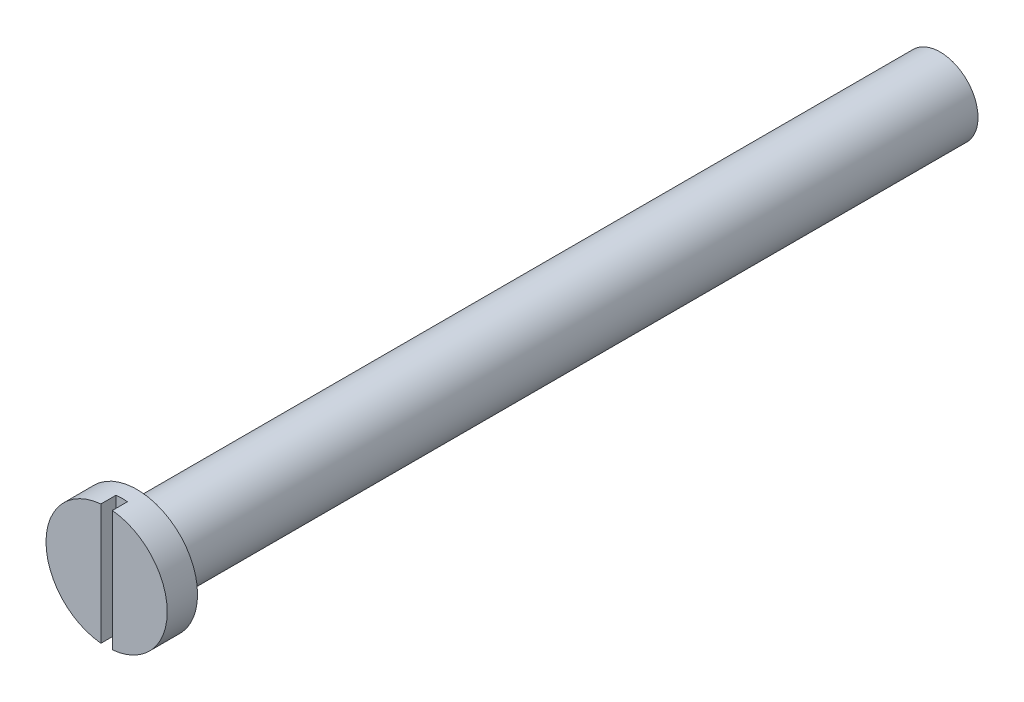
SolidWorks part; units mm, degrees
ref_plane "前视基准面" through (0, 0, 0) normal (0, 0, 1) x (1, 0, 0)
ref_plane "上视基准面" through (0, 0, 0) normal (0, 1, 0) x (1, 0, 0)
ref_plane "右视基准面" through (0, 0, 0) normal (1, 0, 0) x (0, 0, -1)
sketch "草图1" plane through (0, 0, 0) normal (0, 0, 1) x (1, 0, 0)
  circle A0 centre (0, 0) radius 5
  dimension "D1" = 10
extrude "凸台-拉伸1" add sketch "草图1" along normal blind 106
cosmetic thread "装饰螺纹线2" parameters "D1"=10, "D2"=4.134
sketch "草图2" plane through (0, 0, 106) normal (0, 0, 1) x (1, 0, 0)
  circle A0 centre (0, 0) radius 8
  dimension "D1" = 16
extrude "凸台-拉伸2" add sketch "草图2" along normal blind 4
sketch "草图4" plane through (0, 0, 110) normal (0, 0, 1) x (1, 0, 0)
  line L1 (-0.75, 9.78) -> (0.75, 9.78)
  line L2 (-0.75, 9.78) -> (-0.75, -9.78)
  line L3 (-0.75, -9.78) -> (0.75, -9.78)
  line L4 (0.75, 9.78) -> (0.75, -9.78)
  line L5 (-0.75, 9.78) -> (0.75, -9.78) construction
  line L6 (-0.75, -9.78) -> (0.75, 9.78) construction
  point P0 (0, 0)
  dimension "D1" = 1.5
extrude "切除-拉伸1" cut sketch "草图4" against normal blind 2
sketch "草图5" plane through (0, 0, 0) normal (0, 0, -1) x (-1, 0, 0)
  point P0 (0, 0)
  point P1 (-8.9921, 4.042)
hole_wizard "M8 螺纹孔的螺纹孔钻头1" positions "草图6" profile "草图8" hole size "M8" standard "GB"
sketch "草图6" plane through (0, 0, 0) normal (0, 0, -1) x (-1, 0, 0)
  point P0 (0, 0)
sketch "草图8" plane through (0, 0, 0) normal (1, 0, 0) x (0, 1, 0)
  line L0 (0, 0) -> (0, 17.0429)
  line L1 (0, 17.0429) -> (3.4, 15)
  line L2 (3.4, 15) -> (3.4, 0)
  line L5 (3.4, 0) -> (0, 0)
  line L10 (0, 17.0429) -> (-3.4, 15) construction
  line L11 (0, -6.35) -> (0, 107.95) construction
  dimension "孔直径" = 6.8
  dimension "孔深度" = 15
  dimension "导头角度" = 118
